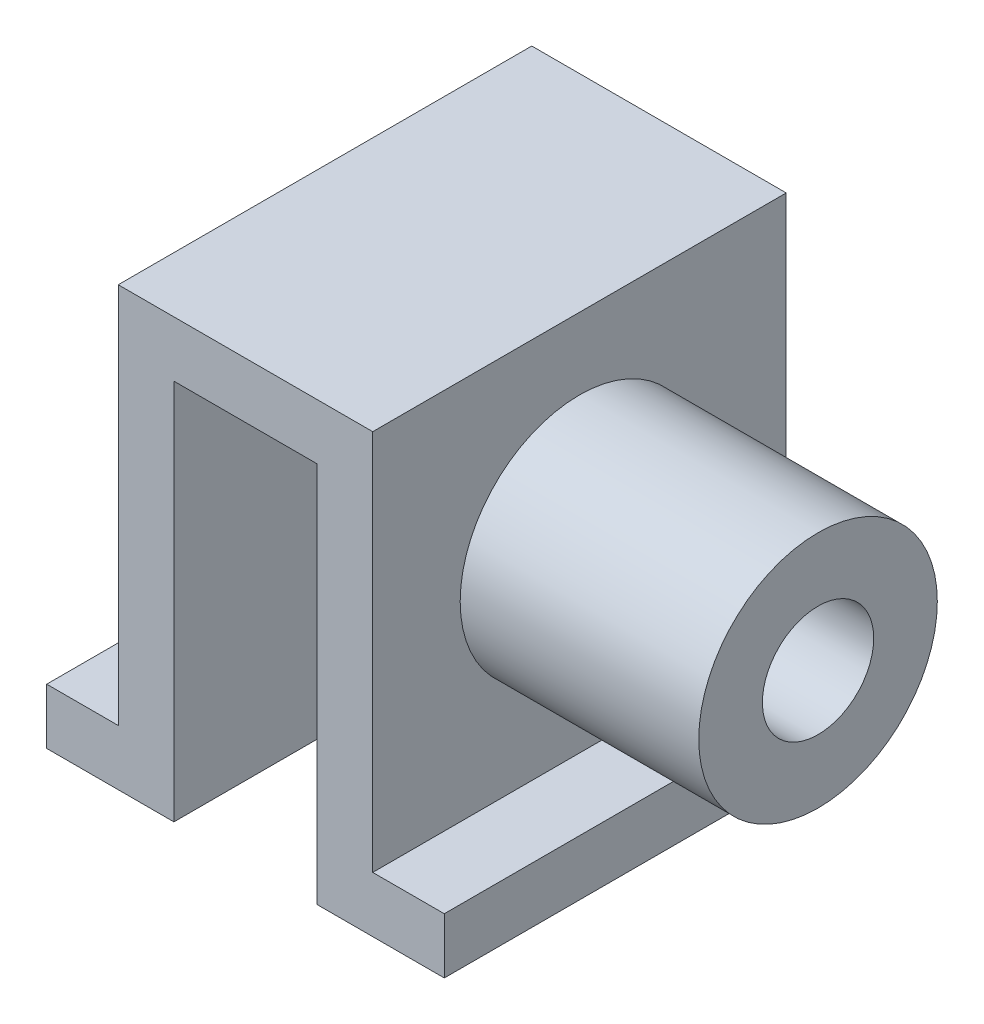
SolidWorks part; units mm, degrees
ref_plane "Front Plane" through (0, 0, 0) normal (0, 0, 1) x (1, 0, 0)
ref_plane "Top Plane" through (0, 0, 0) normal (0, 1, 0) x (1, 0, 0)
ref_plane "Right Plane" through (0, 0, 0) normal (1, 0, 0) x (0, 0, -1)
sketch "Sketch1" plane through (0, 0, 0) normal (0, 0, 1) x (1, 0, 0)
  line L0 (-25, 0) -> (-9, 0)
  line L1 (16, 0) -> (16, 48) construction
  line L2 (9, 7) -> (9, 48)
  line L3 (-9, 7) -> (-9, 48)
  line L4 (-25, 7) -> (-16, 7)
  line L5 (9, 0) -> (9, 48) construction
  line L6 (16, 7) -> (16, 48)
  line L7 (-16, 7) -> (-16, 48)
  line L8 (-9, 0) -> (-9, 48) construction
  line L9 (-16, 0) -> (-16, 48) construction
  line L10 (-25, 7) -> (-25, 0)
  line L11 (-25, 7) -> (25, 7) construction
  line L12 (16, 7) -> (25, 7)
  line L13 (25, 7) -> (25, 0)
  line L14 (-9, 7) -> (-9, 0)
  line L15 (9, 7) -> (9, 0)
  line L16 (9, 0) -> (25, 0)
  line L17 (-25, 0) -> (25, 0) construction
  line L18 (-9, 48) -> (9, 48)
  line L19 (-16, 48) -> (-16, 55)
  line L20 (-16, 55) -> (16, 55)
  line L21 (16, 55) -> (16, 48)
  point P4 (0, 0)
  dimension "D1" = 50
  dimension "D2" = 48
  dimension "D3" = 7
  dimension "D7" = 9
  dimension "D8" = 48
  dimension "D4" = 7
  dimension "D5" = 7
  dimension "D6" = 7
extrude "Boss-Extrude1" add sketch "Sketch1" along normal mid plane 52
sketch "Sketch2" plane through (16, 0, 0) normal (1, 0, 0) x (0, 0, -1)
  line L0 (-26, 55) -> (26, 55) construction
  circle A0 centre (0, 31) radius 15
  circle A1 centre (0, 31) radius 7
  dimension "D2" = 30
  dimension "D3" = 14
  dimension "D1" = 24
extrude "Boss-Extrude2" add sketch "Sketch2" along normal blind 30
sketch "Sketch3" plane through (16, 0, 0) normal (1, 0, 0) x (0, 0, -1)
  circle A1 centre (0, 31) radius 7
  circle A2 centre (0, 31) radius 7
  dimension "D1" = 0
extrude "Cut-Extrude1" cut sketch "Sketch3" against normal up to next
